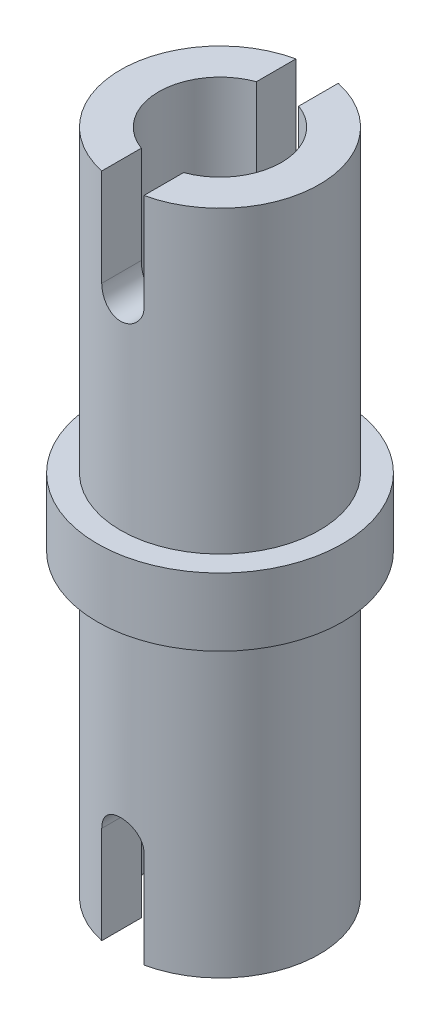
SolidWorks part; units mm, degrees
ref_plane "Front Plane" through (0, 0, 0) normal (0, 0, 1) x (1, 0, 0)
ref_plane "Top Plane" through (0, 0, 0) normal (0, 1, 0) x (1, 0, 0)
ref_plane "Right Plane" through (0, 0, 0) normal (1, 0, 0) x (0, 0, -1)
sketch "Sketch1" plane through (0, 0, 0) normal (0, 1, 0) x (1, 0, 0)
  circle A0 centre (0, 0) radius 2.35
  circle A1 centre (0, 0) radius 1.45
  dimension "D1" = 4.7
  dimension "D2" = 0.9
extrude "Boss-Extrude1" add sketch "Sketch1" along normal mid plane 15.76
sketch "Sketch2" plane through (0, 0, 0) normal (0, 1, 0) x (1, 0, 0)
  circle A0 centre (0, 0) radius 2.9
  circle A1 centre (0, 0) radius 2.35 construction
  circle A2 centre (0, 0) radius 2.35
  dimension "D1" = 5.8
extrude "Boss-Extrude2" add sketch "Sketch2" along normal mid plane 1.6
sketch "Sketch3" plane through (0, 0, 0) normal (0, 0, 1) x (1, 0, 0)
  line L0 (0, 7.88) -> (0, 5.58) construction
  line L1 (2.35, 7.88) -> (-2.35, 7.88) construction
  line L2 (0.5, 7.88) -> (0.5, 5.58)
  line L3 (-0.5, 7.88) -> (-0.5, 5.58)
  line L4 (-2.9, 0) -> (10.6474, 0) construction
  line L5 (-2.9, 0.8) -> (-2.9, -0.8) construction
  line L6 (0, -7.88) -> (0, -5.58) construction
  line L7 (0.5, -7.88) -> (0.5, -5.58)
  line L8 (-0.5, -7.88) -> (-0.5, -5.58)
  arc A0 (0.5, 7.88) -> (-0.5, 7.88) centre (0, 7.88) ccw
  arc A1 (-0.5, 5.58) -> (0.5, 5.58) centre (0, 5.58) ccw
  arc A2 (0.5, -7.88) -> (-0.5, -7.88) centre (0, -7.88) cw
  arc A3 (-0.5, -5.58) -> (0.5, -5.58) centre (0, -5.58) cw
  point P5 (0, 6.73)
  point P11 (0, 5.08)
  point P17 (0, -6.73)
  dimension "D1" = 2.8
  dimension "D2" = 1
extrude "Cut-Extrude1" cut sketch "Sketch3" against normal mid plane 21.6
